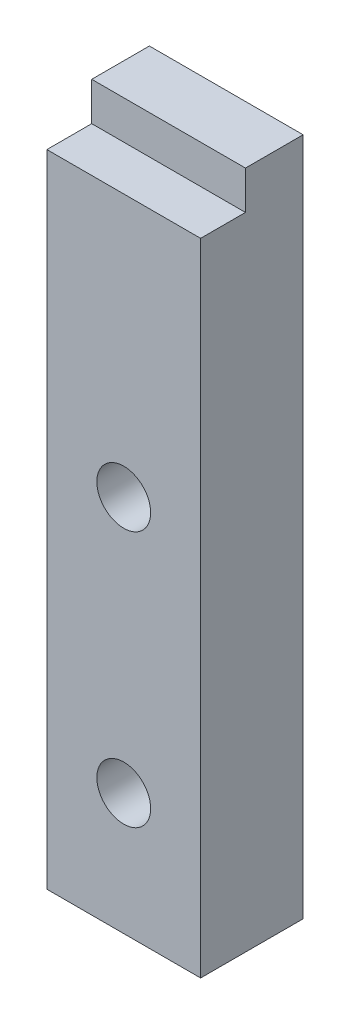
SolidWorks part; units mm, degrees
ref_plane "Płaszczyzna przednia" through (0, 0, 0) normal (0, 0, 1) x (1, 0, 0)
ref_plane "Płaszczyzna górna" through (0, 0, 0) normal (0, 1, 0) x (1, 0, 0)
ref_plane "Płaszczyzna prawa" through (0, 0, 0) normal (1, 0, 0) x (0, 0, -1)
sketch "Sketch1" plane through (0, 0, 0) normal (0, 0, 1) x (1, 0, 0)
  line L0 (6, 50) -> (6, 29.5) construction
  line L1 (0, 0) -> (12, 0)
  line L2 (0, 0) -> (0, 50)
  line L3 (0, 50) -> (12, 50)
  line L4 (12, 0) -> (12, 50)
  line L5 (6, 29.5) -> (6, 9.5) construction
  circle A0 centre (6, 29.5) radius 2.1
  circle A1 centre (6, 9.5) radius 2.1
  dimension "D3" = 4.2
  dimension "D1" = 50
  dimension "D2" = 12
  dimension "D4" = 20.5
  dimension "D5" = 40.5
extrude "Boss-Extrude1" add sketch "Sketch1" along normal blind 8
sketch "Sketch2" plane through (0, 50, 0) normal (0, 1, 0) x (1, 0, 0)
  line L0 (12, -8) -> (12, 0) construction
  line L1 (0, 0) -> (12, 0)
  line L2 (0, 0) -> (0, -4.5)
  line L3 (0, -4.5) -> (12, -4.5)
  line L4 (12, 0) -> (12, -4.5)
  line L5 (12, -8) -> (0, -8) construction
  dimension "D1" = 3.5
extrude "Boss-Extrude2" add sketch "Sketch2" along normal blind 3
